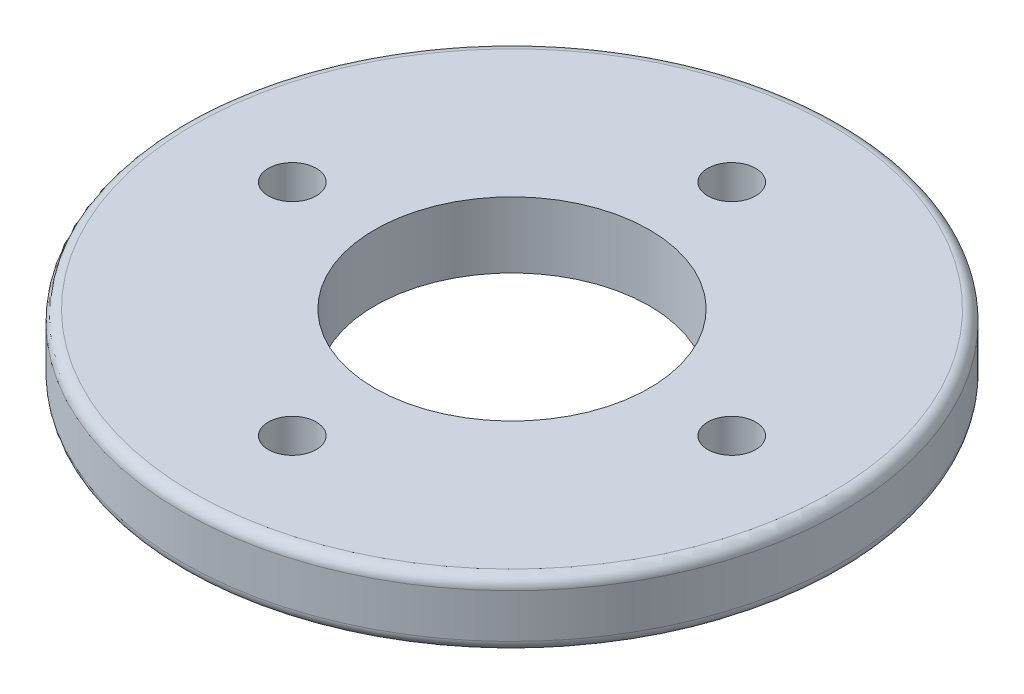
SolidWorks part; units mm, degrees
ref_plane "Front" through (0, 0, 0) normal (0, 0, 1) x (1, 0, 0)
ref_plane "Top" through (0, 0, 0) normal (0, 1, 0) x (1, 0, 0)
ref_plane "Right" through (0, 0, 0) normal (1, 0, 0) x (0, 0, -1)
sketch "Sketch1" plane through (0, 0, 0) normal (0, 1, 0) x (1, 0, 0)
  circle A0 centre (0, 0) radius 15
  dimension "D1" = 30
extrude "Boss-Extrude1" add sketch "Sketch1" along normal blind 3
sketch "Sketch2" plane through (0, 3, 0) normal (0, 1, 0) x (1, 0, 0)
  line L0 (0, 0) -> (0, 15) construction
  circle A0 centre (0, 0) radius 15 construction
  circle A1 centre (0, 10) radius 1.09
  dimension "D1" = 2.18
  dimension "D2" = 10
extrude "Cut-Extrude1" cut sketch "Sketch2" against normal up to surface (3 mm away) up to face at (0, 0, 15)
sketch "Sketch3" plane through (0, 3, 0) normal (0, 1, 0) x (1, 0, 0)
  point P0 (0, 0)
sketch "Sketch4" plane through (0, 0, 0) normal (0, 0, 1) x (1, 0, 0)
  line L0 (0, 0) -> (0, 3) construction
pattern_circular "CirPattern1" count 4 over 360 about axis through (0, 0, 0) along (0, 1, 0) of "Cut-Extrude1"
fillet "Fillet1" radius 0.5 2 edges at (0, 0, 15) (0, 3, 15)
sketch "Sketch5" plane through (0, 3, 0) normal (0, 1, 0) x (1, 0, 0)
  circle A0 centre (0, 0) radius 6.25
  dimension "D1" = 12.5
extrude "Cut-Extrude2" cut sketch "Sketch5" against normal mid plane 50
